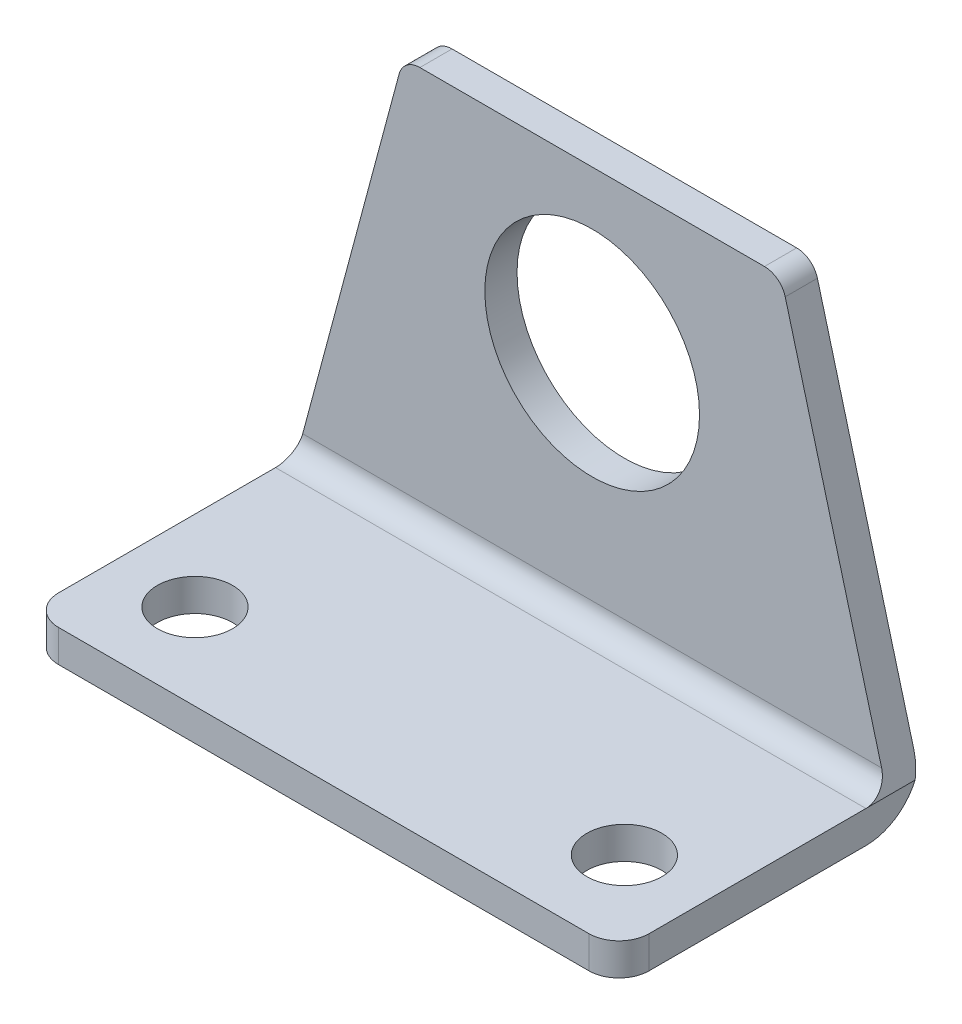
SolidWorks part; units mm, degrees
ref_plane "前视基准面" through (0, 0, 0) normal (0, 0, 1) x (1, 0, 0)
ref_plane "上视基准面" through (0, 0, 0) normal (0, 1, 0) x (1, 0, 0)
ref_plane "右视基准面" through (0, 0, 0) normal (1, 0, 0) x (0, 0, -1)
sketch "草图1" plane through (0, 0, 0) normal (0, 0, 1) x (1, 0, 0)
  line L0 (0, 0) -> (0, 40) construction
  line L1 (-27.5, 0) -> (27.5, 0) construction
  circle A0 centre (0, 25) radius 10
  point P5 (-20, 0)
  dimension "L" = 20
  dimension "BE" = 55
  dimension "BF" = 40
  dimension "BH" = 40
  dimension "BG" = 25
sketch "草图2" plane through (0, 0, 0) normal (1, 0, 0) x (0, 0, -1)
  line L0 (0, 0) -> (-28, 0) construction
  line L1 (-20, 0) -> (-20, 3) construction
  point P5 (-16.5, 0)
  dimension "BB" = 3
  dimension "BD" = 8
  dimension "BC" = 20
  dimension "AA" = 7
sketch "草图3" plane through (0, 0, 0) normal (1, 0, 0) x (0, 0, -1)
  line L0 (-28, 0) -> (-5, 0)
  line L1 (0, 5) -> (0, 40)
  line L2 (0, 0) -> (0, 40) construction
  line L3 (-28, 0) -> (-28, 3)
  line L4 (-28, 3) -> (-5, 3)
  line L5 (-3, 5) -> (-3, 40)
  line L6 (-3, 40) -> (0, 40)
  arc A0 (-5, 3) -> (-3, 5) centre (-5, 5) ccw
  arc A1 (-5, 0) -> (0, 5) centre (-5, 5) ccw
  dimension "D1" = 4
extrude "凸台-拉伸1" add sketch "草图3" against normal up to vertex (27.5 mm away) from vertex at 27.5 starting at point (27.5, 0, 0)
sketch "草图4" plane through (0, 0, 3) normal (0, 0, 1) x (1, 0, 0)
  circle A0 centre (0, 25) radius 10 construction
  circle A1 centre (0, 25) radius 10
extrude "切除-拉伸1" cut sketch "草图4" against normal through all
sketch "草图5" plane through (0, 0, 3) normal (0, 0, 1) x (1, 0, 0)
  line L0 (-17.5859, 40) -> (-27.5, 3)
  line L1 (-27.5, 40) -> (27.5, 40) construction
  line L2 (0, 0) -> (0, 25) construction
  line L3 (17.5859, 40) -> (27.5, 3)
  line L4 (-27.5, 3) -> (-27.5, 50)
  line L5 (-27.5, 50) -> (27.5, 50)
  line L6 (27.5, 50) -> (27.5, 3)
  line L7 (-17.5859, 40) -> (17.5859, 40)
  dimension "D1" = 30
  dimension "D2" = 10
extrude "切除-拉伸2" cut sketch "草图5" against normal through all and the other way through all
sketch "草图6" plane through (0, 3, 0) normal (0, 1, 0) x (1, 0, 0)
  line L0 (0, 0) -> (0, -16.5) construction
  circle A0 centre (-20, -20) radius 3.5
  circle A1 centre (20, -20) radius 3.5
  point P2 (-20, -16.5)
  point P11 (20, -16.5)
extrude "切除-拉伸3" cut sketch "草图6" against normal through all
fillet "圆角1" radius 2 2 edges at (17.5859, 40, 1.5) (-17.5859, 40, 1.5)
fillet "圆角2" radius 2.8 2 edges at (27.5, 1.5, 28) (-27.5, 1.5, 28)
